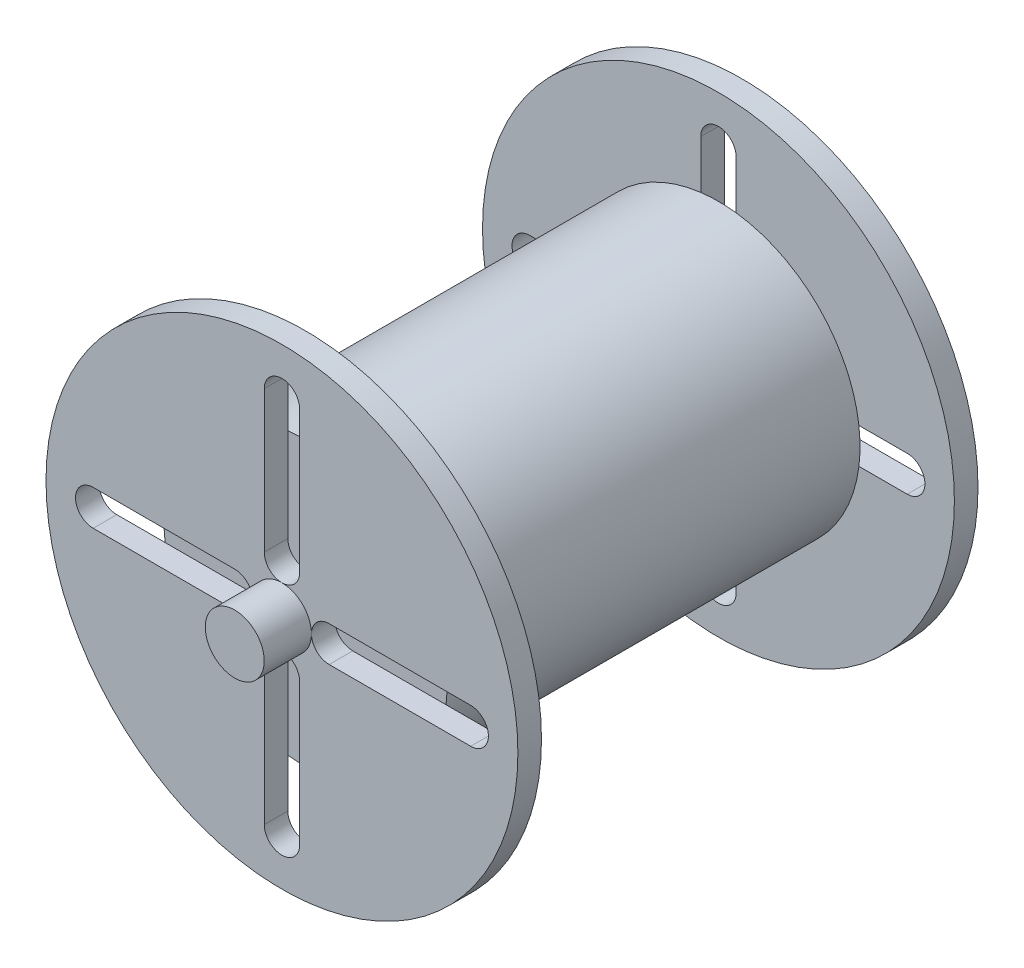
SolidWorks part; units mm, degrees
ref_plane "Front Plane" through (0, 0, 0) normal (0, 0, 1) x (1, 0, 0)
ref_plane "Top Plane" through (0, 0, 0) normal (0, 1, 0) x (1, 0, 0)
ref_plane "Right Plane" through (0, 0, 0) normal (1, 0, 0) x (0, 0, -1)
sketch "Sketch1" plane through (0, 0, 0) normal (0, 0, 1) x (1, 0, 0)
  circle A0 centre (0, 0) radius 60
  dimension "D1" = 120
extrude "Boss-Extrude1" add sketch "Sketch1" along normal mid plane 175
sketch "Sketch2" plane through (0, 0, 87.5) normal (0, 0, 1) x (1, 0, 0)
  line L0 (0, 0) -> (0, 100) construction
  line L1 (0, 80) -> (0, 20) construction
  line L2 (7.5, 80) -> (7.5, 20)
  line L3 (-7.5, 80) -> (-7.5, 20)
  line L4 (80, 7.5) -> (20, 7.5)
  line L5 (80, -7.5) -> (20, -7.5)
  line L6 (80, 0) -> (20, 0) construction
  line L7 (7.5, -80) -> (7.5, -20)
  line L8 (-7.5, -80) -> (-7.5, -20)
  line L9 (0, -80) -> (0, -20) construction
  line L10 (-80, -7.5) -> (-20, -7.5)
  line L11 (-80, 7.5) -> (-20, 7.5)
  line L12 (-80, 0) -> (-20, 0) construction
  circle A0 centre (0, 0) radius 100
  arc A1 (7.5, 80) -> (-7.5, 80) centre (0, 80) ccw
  arc A2 (-7.5, 20) -> (7.5, 20) centre (0, 20) ccw
  arc A3 (80, -7.5) -> (80, 7.5) centre (80, 0) ccw
  arc A4 (20, 7.5) -> (20, -7.5) centre (20, 0) ccw
  arc A5 (-7.5, -80) -> (7.5, -80) centre (0, -80) ccw
  arc A6 (7.5, -20) -> (-7.5, -20) centre (0, -20) ccw
  arc A7 (-80, 7.5) -> (-80, -7.5) centre (-80, 0) ccw
  arc A8 (-20, -7.5) -> (-20, 7.5) centre (-20, 0) ccw
  point P6 (0, 50)
  point P16 (50, 0)
  point P23 (0, -50)
  point P30 (-50, 0)
  point P35 (0, 0)
  dimension "D1" = 200
  dimension "D2" = 20
  dimension "D3" = 20
  dimension "D4" = 15
  dimension "D5" = 4
extrude "Boss-Extrude2" add sketch "Sketch2" along normal blind 10
sketch "Sketch3" plane through (0, 0, 97.5) normal (0, 0, 1) x (1, 0, 0)
  circle A0 centre (0, 0) radius 12.5
extrude "Boss-Extrude3" add sketch "Sketch3" along normal blind 20
mirror "Mirror1" about plane through (0, 0, 0) normal (0, 0, 1) of "Boss-Extrude2"
mirror "Mirror2" about plane through (0, 0, 0) normal (0, 0, 1) of "Boss-Extrude3"
